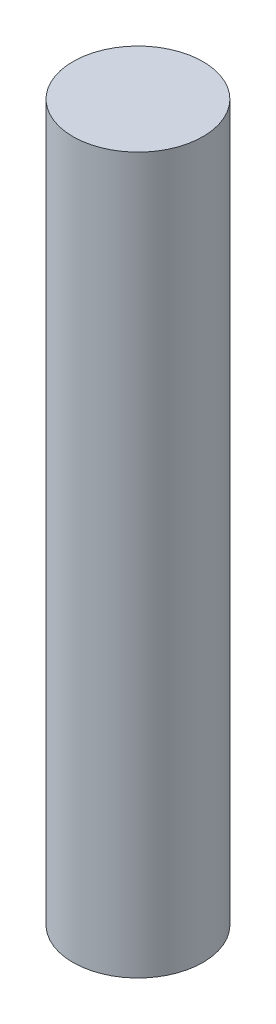
SolidWorks part; units mm, degrees
ref_plane "Front Plane" through (0, 0, 0) normal (0, 0, 1) x (1, 0, 0)
ref_plane "Top Plane" through (0, 0, 0) normal (0, 1, 0) x (1, 0, 0)
ref_plane "Right Plane" through (0, 0, 0) normal (1, 0, 0) x (0, 0, -1)
sketch "Sketch1" plane through (0, 0, 0) normal (0, 1, 0) x (1, 0, 0)
  circle A0 centre (0, 0) radius 2
  dimension "D1" = 4
extrude "Boss-Extrude1" add sketch "Sketch1" along normal blind 22
